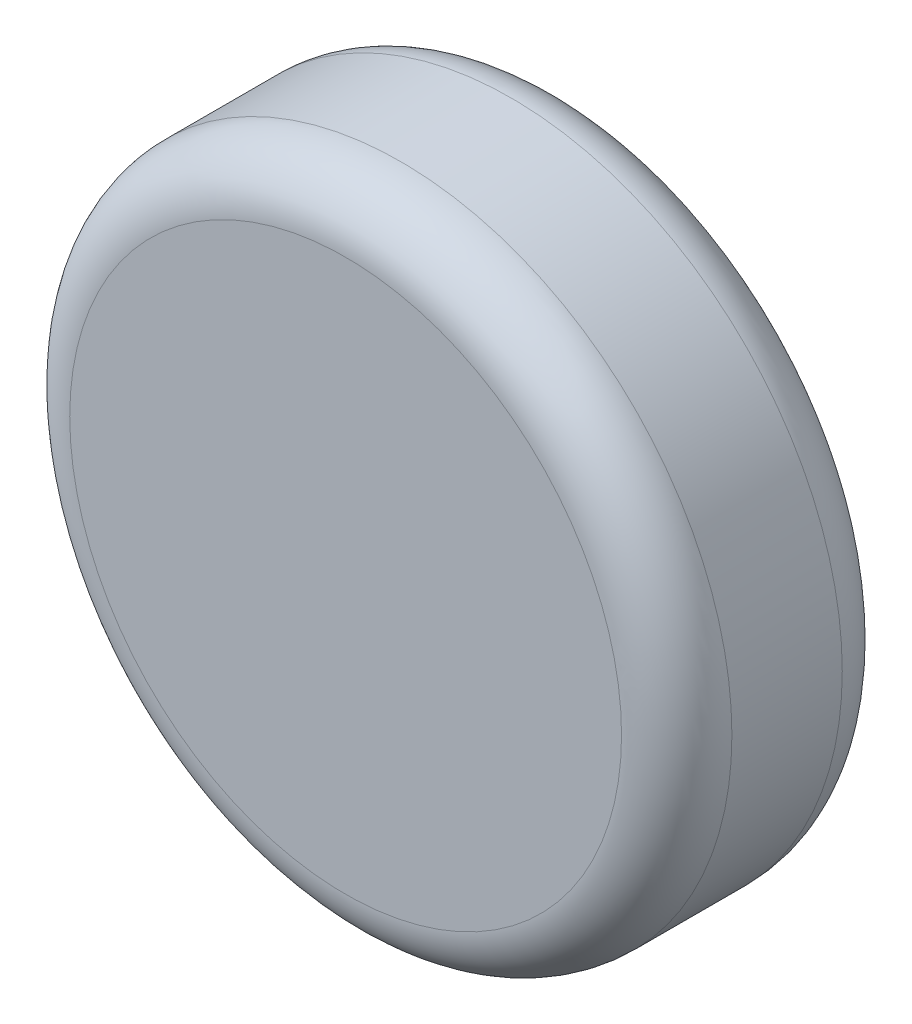
SolidWorks part; units mm, degrees
material "Rubber"
ref_plane "Front" through (0, 0, 0) normal (0, 0, 1) x (1, 0, 0)
ref_plane "Top" through (0, 0, 0) normal (0, 1, 0) x (1, 0, 0)
ref_plane "Right" through (0, 0, 0) normal (1, 0, 0) x (0, 0, -1)
sketch "Sketch1" plane through (0, 0, 0) normal (0, 0, 1) x (1, 0, 0)
  circle A0 centre (0, 0) radius 76.2
  dimension "D1" = 152.4
extrude "Boss-Extrude1" add sketch "Sketch1" along normal blind 50.8
fillet "Fillet1" radius 12.7 2 edges at (76.2, 0, 0) (76.2, 0, 50.8)
